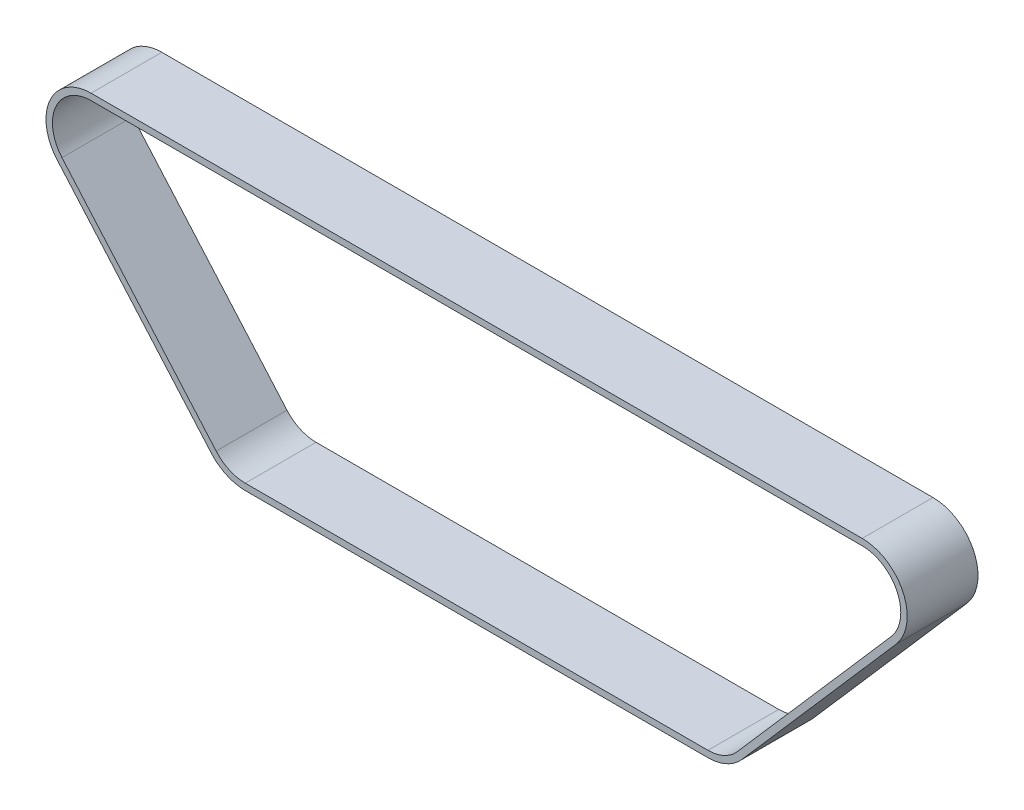
SolidWorks part; units mm, degrees
ref_plane "前视基准面" through (0, 0, 0) normal (0, 0, 1) x (1, 0, 0)
ref_plane "上视基准面" through (0, 0, 0) normal (0, 1, 0) x (1, 0, 0)
ref_plane "右视基准面" through (0, 0, 0) normal (1, 0, 0) x (0, 0, -1)
sketch "草图1" plane through (0, 0, 0) normal (0, 0, 1) x (1, 0, 0)
  line L0 (-89.6447, 149) -> (389.6447, 149)
  line L3 (6.2132, -9) -> (293.7868, -9)
  line L4 (-107.7384, 109.2325) -> (-11.8806, -0.7675)
  line L5 (311.8806, -0.7675) -> (407.7384, 109.2325)
  line L6 (-89.6447, 153) -> (389.6447, 153)
  line L7 (-110.7541, 106.6045) -> (-14.8962, -3.3955)
  line L8 (6.2132, -13) -> (293.7868, -13)
  line L9 (314.8962, -3.3955) -> (410.7541, 106.6045)
  arc A17 (-89.6447, 149) -> (-107.7384, 109.2325) centre (-89.6447, 125) ccw
  arc A18 (407.7384, 109.2325) -> (389.6447, 149) centre (389.6447, 125) ccw
  arc A19 (293.7868, -9) -> (311.8806, -0.7675) centre (293.7868, 15) ccw
  arc A20 (-11.8806, -0.7675) -> (6.2132, -9) centre (6.2132, 15) ccw
  arc A21 (410.7541, 106.6045) -> (389.6447, 153) centre (389.6447, 125) ccw
  arc A22 (-89.6447, 153) -> (-110.7541, 106.6045) centre (-89.6447, 125) ccw
  arc A23 (-14.8962, -3.3955) -> (6.2132, -13) centre (6.2132, 15) ccw
  arc A24 (293.7868, -13) -> (314.8962, -3.3955) centre (293.7868, 15) ccw
  dimension "D2" = 48
  dimension "D1" = 4
extrude "凸台-拉伸1" add sketch "草图1" along normal blind 44
